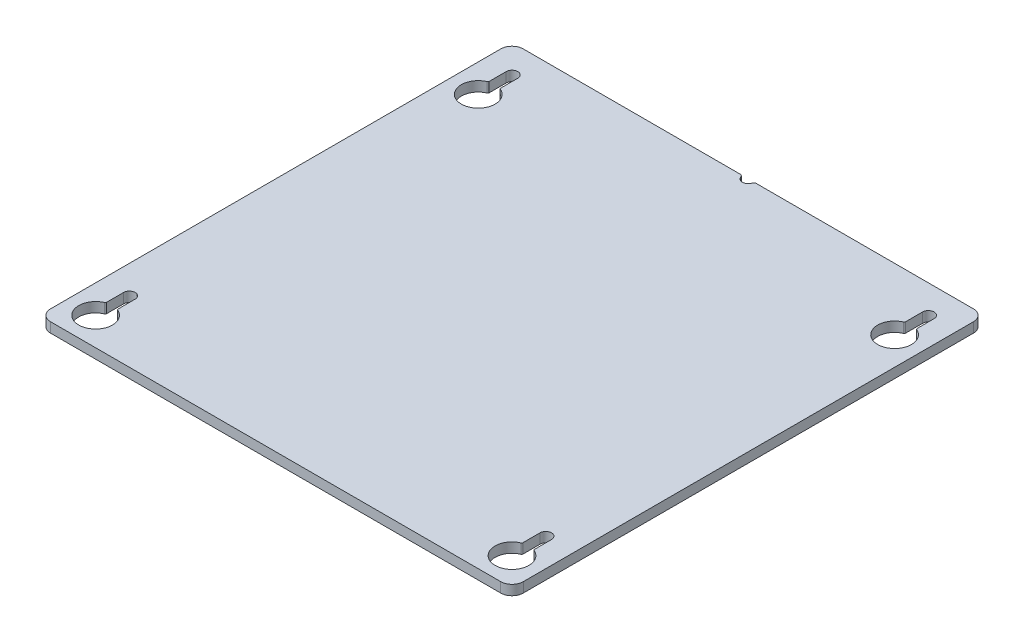
SolidWorks part; units mm, degrees
material "ABS PC"
ref_plane "Front Plane" through (0, 0, 0) normal (0, 0, 1) x (1, 0, 0)
ref_plane "Top Plane" through (0, 0, 0) normal (0, 1, 0) x (1, 0, 0)
ref_plane "Right Plane" through (0, 0, 0) normal (1, 0, 0) x (0, 0, -1)
sketch "Sketch1" plane through (0, 0, 0) normal (0, 1, 0) x (1, 0, 0)
  line L0 (133.35, 266.7) -> (133.35, 0) construction
  line L1 (0, 0) -> (266.7, 0)
  line L2 (0, 0) -> (0, 266.7)
  line L3 (0, 266.7) -> (266.7, 266.7)
  line L4 (266.7, 0) -> (266.7, 266.7)
  line L5 (0, 266.7) -> (31.75, 234.95) construction
  line L6 (31.75, 234.95) -> (234.95, 234.95) construction
  line L7 (31.75, 234.95) -> (31.75, 31.75) construction
  line L8 (31.75, 31.75) -> (234.95, 31.75) construction
  line L9 (234.95, 234.95) -> (234.95, 31.75) construction
  line L10 (31.75, 234.95) -> (234.95, 31.75) construction
  line L11 (31.75, 31.75) -> (234.95, 234.95) construction
  line L12 (234.95, 234.95) -> (266.7, 266.7) construction
  line L13 (31.75, 31.75) -> (0, 0) construction
  line L14 (234.95, 31.75) -> (266.7, 0) construction
  circle A0 centre (15.875, 250.825) radius 3.2639
  circle A1 centre (250.825, 250.825) radius 3.2639
  circle A2 centre (15.875, 15.875) radius 3.2639
  circle A3 centre (250.825, 15.875) radius 3.2639
  point P7 (133.35, 133.35)
  dimension "D3" = 6.5278
  dimension "D1" = 266.7
  dimension "D2" = 203.2
extrude "Boss-Extrude1" add sketch "Sketch1" along normal blind 5.588
fillet "Fillet1" radius 6.35 4 edges at (0, 2.794, -266.7) (266.7, 2.794, -266.7) (0, 2.794, 0) (266.7, 2.794, 0)
sketch "Sketch5" plane through (0, 5.588, 0) normal (0, 1, 0) x (1, 0, 0)
  line L0 (19.1389, 34.925) -> (19.1389, 24.8233)
  line L1 (12.6111, 34.925) -> (12.6111, 24.8233)
  line L2 (254.0889, 34.925) -> (254.0889, 24.8233)
  line L3 (247.5611, 34.925) -> (247.5611, 24.8233)
  line L4 (19.1389, 250.825) -> (19.1389, 240.7233)
  line L5 (12.6111, 250.825) -> (12.6111, 240.7233)
  line L6 (254.0889, 250.825) -> (254.0889, 240.7233)
  line L7 (247.5611, 250.825) -> (247.5611, 240.7233)
  arc A0 (12.6111, 24.8233) -> (19.1389, 24.8233) centre (15.875, 15.875) ccw
  arc A1 (19.1389, 34.925) -> (12.6111, 34.925) centre (15.875, 34.925) ccw
  circle A2 centre (15.875, 34.925) radius 9.525 construction
  arc A3 (254.0889, 34.925) -> (247.5611, 34.925) centre (250.825, 34.925) ccw
  arc A4 (247.5611, 24.8233) -> (254.0889, 24.8233) centre (250.825, 15.875) ccw
  circle A5 centre (250.825, 34.925) radius 9.525 construction
  arc A6 (12.6111, 240.7233) -> (19.1389, 240.7233) centre (15.875, 231.775) ccw
  circle A7 centre (15.875, 250.825) radius 9.525 construction
  arc A8 (19.1389, 250.825) -> (12.6111, 250.825) centre (15.875, 250.825) ccw
  arc A9 (247.5611, 240.7233) -> (254.0889, 240.7233) centre (250.825, 231.775) ccw
  circle A10 centre (250.825, 250.825) radius 9.525 construction
  arc A11 (254.0889, 250.825) -> (247.5611, 250.825) centre (250.825, 250.825) ccw
  dimension "D1" = 19.05
  dimension "D2" = 6.5278
  dimension "D3" = 19.05
extrude "Cut-Extrude2" cut sketch "Sketch5" against normal through all
sketch "Sketch6" plane through (0, 5.588, 0) normal (0, 1, 0) x (1, 0, 0)
  line L0 (260.35, 266.7) -> (6.35, 266.7) construction
  circle A0 centre (133.35, 266.7) radius 3.302
  dimension "D1" = 6.604
extrude "Cut-Extrude3" cut sketch "Sketch6" against normal through all
fillet "Fillet2" radius 1.5875 2 edges at (130.048, 2.794, -266.7) (136.652, 2.794, -266.7)
fillet "Fillet3" radius 0.762 8 edges at (12.6111, 2.794, -24.8233) (19.1389, 2.794, -24.8233) (247.5611, 2.794, -240.7233) (247.5611, 2.794, -24.8233) (254.0889, 2.794, -24.8233) (254.0889, 2.794, -240.7233) (19.1389, 2.794, -240.7233) (12.6111, 2.794, -240.7233)
